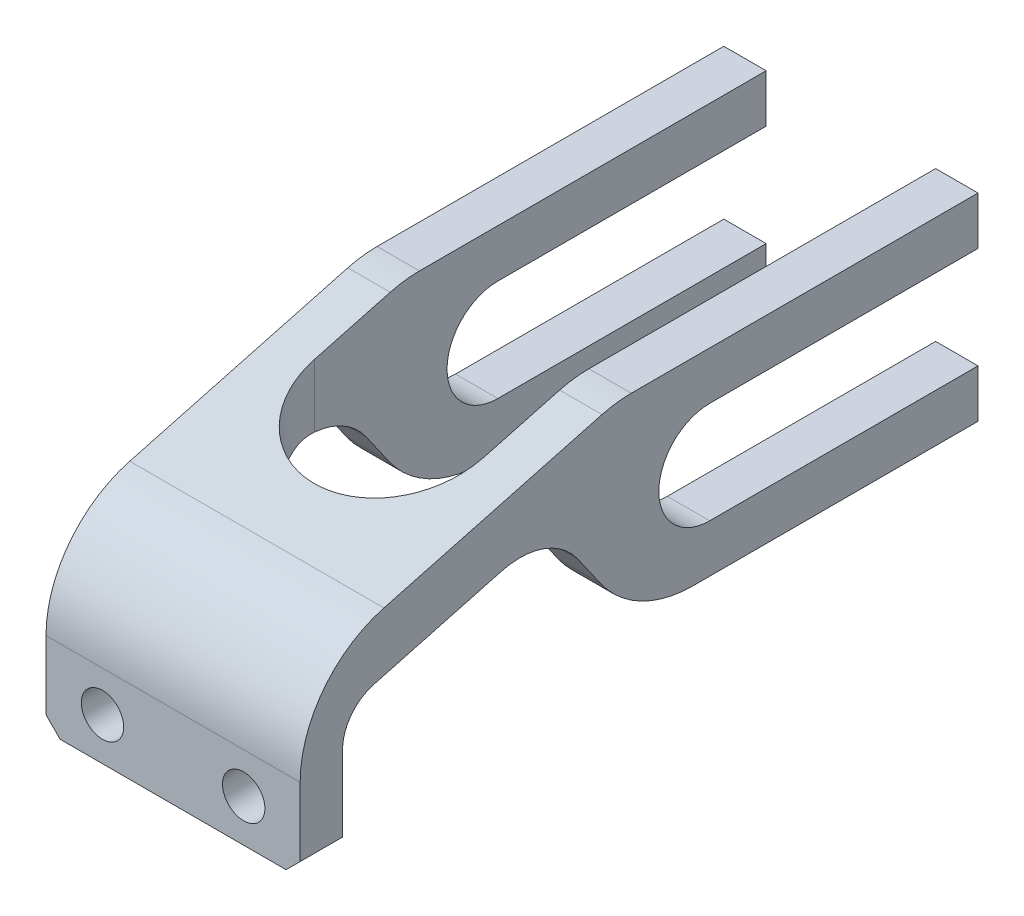
SolidWorks part; units mm, degrees
material "AISI 304"
ref_plane "前视基准面" through (0, 0, 0) normal (0, 0, 1) x (1, 0, 0)
ref_plane "上视基准面" through (0, 0, 0) normal (0, 1, 0) x (1, 0, 0)
ref_plane "右视基准面" through (0, 0, 0) normal (1, 0, 0) x (0, 0, -1)
sketch "草图1" plane through (0, 0, 0) normal (0, 0, 1) x (1, 0, 0)
  line L0 (0, 6) -> (0, -6) construction
  line L1 (-9, 6) -> (9, 6)
  line L2 (-9, 6) -> (-9, -6)
  line L3 (-9, -6) -> (9, -6)
  line L4 (9, 6) -> (9, -6)
  dimension "D1" = 18
  dimension "D2" = 12
extrude "拉伸1" add sketch "草图1" along normal blind 3
sketch "草图2" plane through (0, 0, 0) normal (1, 0, 0) x (0, 0, -1)
  line L0 (19.3923, 12) -> (45, 12)
  line L1 (45, 12) -> (45, 8.2)
  line L2 (0, -6) -> (0, 6) construction
  line L4 (45, 8.2) -> (20.6653, 8.2)
  line L6 (-3, 6) -> (19.3923, 12)
  line L7 (20.6653, 8.2) -> (0, 2.6627)
  line L8 (-3, 6) -> (0, 2.6627)
  line L9 (-3, -6) -> (-3, 6) construction
  line L10 (-3, -6) -> (0, -6) construction
  dimension "D1" = 45
  dimension "D2" = 3.8
  dimension "D3" = 4
  dimension "D4" = 75
  dimension "D5" = 18
extrude "拉伸2" add sketch "草图2" along normal mid plane 18
fillet "圆角1" [suppressed] radius 5
sketch "草图3" plane through (9, 0, 0) normal (1, 0, 0) x (0, 0, -1)
  line L0 (45, 8.2) -> (45, 12) construction
  line L1 (45, 11.85) -> (23.5, 11.85)
  line L2 (45, 11.85) -> (45, 8.35)
  line L3 (45, 8.35) -> (23.5, 8.35)
  line L4 (23.5, 11.85) -> (23.5, 8.35) construction
  line L5 (45, 10.1) -> (23.5, 10.1) construction
  line L6 (-3, -6) -> (-3, 6) construction
  arc A0 (23.5, 11.85) -> (23.5, 8.35) centre (23.5, 10.1) ccw
  dimension "D1" = 3.5
  dimension "D2" = 26.5
extrude "拉伸3" [suppressed] cut sketch "草图3" against normal up to surface (18 mm away)
sketch "Sketch2" plane through (9, 0, 0) normal (1, 0, 0) x (0, 0, -1)
  line L0 (-3, -6) -> (0, -6) construction
  line L1 (45, 8.2) -> (20.6653, 8.2)
  line L2 (45, 8.2) -> (45, -2)
  line L3 (45, -2) -> (20.6653, -2)
  line L4 (20.6653, 8.2) -> (20.6653, -2) construction
  line L5 (0, 2.6627) -> (20.6653, 8.2) construction
  line L6 (0, 2.6627) -> (20.6653, 8.2) construction
  line L7 (20.6653, -2) -> (14.6515, 6.5886)
  line L8 (0, 2.6627) -> (20.6653, -2) construction
  line L9 (14.6515, 6.5886) -> (20.6653, 8.2)
  point P7 (-1.5, -6)
  dimension "D1" = 4
  dimension "D2" = 35
  dimension "D3" = 110
extrude "Extrude1" add sketch "Sketch2" against normal blind 18
sketch "草图5" plane through (0, 0, 0) normal (0, 0, -1) x (-1, 0, 0)
  line L0 (-5, -3) -> (5, -3) construction
  line L1 (0, 0) -> (0, -3) construction
  line L2 (9, -6) -> (-9, -6) construction
  circle A0 centre (-5, -3) radius 1.5
  circle A1 centre (5, -3) radius 1.5
  dimension "D3" = 3
  dimension "D1" = 3
  dimension "D2" = 10
extrude "拉伸5" cut sketch "草图5" against normal up to surface (3 mm away) up to face at (0, 0, 3)
chamfer "倒角1" distance 1 angle 45 2 edges at (-9, -6, 1.5) (9, -6, 1.5)
fillet "Fillet1" radius 8 2 edges at (0, 6, 3) (0, 12, -19.3923)
sketch "Sketch3" plane through (0, -6, 0) normal (0, -1, 0) x (1, 0, 0)
  line L0 (-9, -45) -> (9, -45) construction
  line L1 (-6, -45) -> (6, -45)
  line L2 (-6, -45) -> (-6, -13)
  line L3 (-6, -13) -> (6, -13) construction
  line L4 (6, -45) -> (6, -13)
  line L5 (0, 0) -> (0, -13) construction
  arc A0 (6, -13) -> (-6, -13) centre (0, -13) ccw
  dimension "D1" = 12
  dimension "D2" = 32
extrude "Extrude6" cut sketch "Sketch3" against normal up to surface (18 mm away) up to face at (0, 12, -32.7228)
fillet "Fillet4" [suppressed] radius 3
sketch "Sketch4" plane through (9, 0, 0) normal (1, 0, 0) x (0, 0, -1)
  line L0 (45, 5) -> (23, 5) construction
  line L1 (26, 8.6) -> (45, 8.6)
  line L2 (23, 5.6) -> (23, 4.4) construction
  line L3 (26, 1.4) -> (45, 1.4)
  line L4 (45, 8.6) -> (45, 1.4)
  line L5 (45, -2) -> (45, 12) construction
  line L7 (45, 12) -> (20.4455, 12) construction
  arc A0 (26, 8.6) -> (26, 1.4) centre (26, 5) ccw
  arc A1 (26, 8.6) -> (23, 5.6) centre (26, 5.6) ccw construction
  arc A2 (26, 1.4) -> (23, 4.4) centre (26, 4.4) cw construction
  dimension "D3" = 3
  dimension "D1" = 22
  dimension "D2" = 3.4
extrude "Extrude7" cut sketch "Sketch4" against normal up to surface (18 mm away)
fillet "Fillet5" radius 3 1 edges at (0, 2.6627, 0)
fillet "Fillet6" radius 5 2 edges at (-7.5, 6.5886, -14.6515) (7.5, 6.5886, -14.6515)
fillet "Fillet7" radius 8 2 edges at (7.5, -2, -20.6653) (-7.5, -2, -20.6653)
sketch "Sketch5" plane through (0, 12, 0) normal (0, 1, 0) x (1, 0, 0)
  line L0 (-6, 45) -> (-6, 20.4455) construction
  line L1 (-6, 29) -> (6, 29)
  line L2 (-6, 29) -> (-6, 9)
  line L3 (-6, 9) -> (6, 9) construction
  line L4 (6, 29) -> (6, 9)
  line L5 (6, 20.4455) -> (6, 45) construction
  line L6 (9, 45) -> (6, 45) construction
  arc A0 (-6, 9) -> (6, 9) centre (0, 9) ccw
  dimension "D1" = 16
  dimension "D2" = 20
extrude "Extrude8" [suppressed] cut sketch "Sketch5" against normal blind 10
